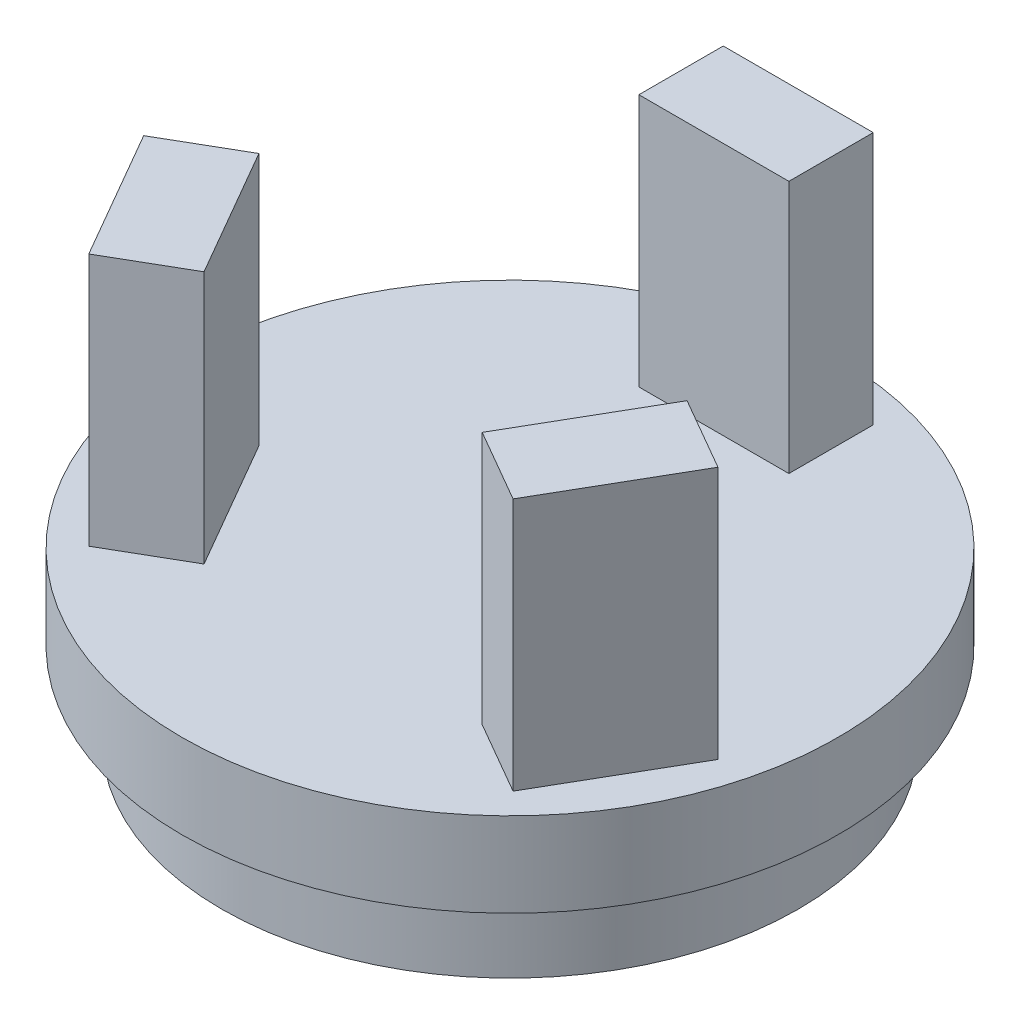
SolidWorks part; units mm, degrees
ref_plane "Plan de face" through (0, 0, 0) normal (0, 0, 1) x (1, 0, 0)
ref_plane "Plan de dessus" through (0, 0, 0) normal (0, 1, 0) x (1, 0, 0)
ref_plane "Plan de droite" through (0, 0, 0) normal (1, 0, 0) x (0, 0, -1)
sketch "Esquisse2" plane through (0, 0, 0) normal (0, 1, 0) x (1, 0, 0)
  circle A0 centre (50.8875, 23.7844) radius 61.5
  dimension "D2" = 123
extrude "Boss.-Extru.1" add sketch "Esquisse2" along normal blind 18
sketch "Esquisse3" plane through (0, 18, 0) normal (0, 1, 0) x (1, 0, 0)
  circle A0 centre (50.8875, 23.7844) radius 70
  circle A1 centre (50.8875, 23.7844) radius 61.5 construction
  dimension "D1" = 0
extrude "Boss.-Extru.2" add sketch "Esquisse3" along normal blind 18
sketch "Esquisse4" plane through (0, 36, 0) normal (0, 1, 0) x (1, 0, 0)
  line L0 (50.8875, 23.7844) -> (50.8875, 85.2844) construction
  line L1 (50.8875, 85.2844) -> (50.8875, 23.7844) construction
  line L2 (50.8875, 23.7844) -> (104.1481, -6.9656) construction
  line L3 (104.1481, -6.9656) -> (50.8875, 23.7844) construction
  line L4 (50.8875, 23.7844) -> (-2.373, -6.9656) construction
  line L5 (104.1481, -6.9656) -> (96.1481, -20.822)
  line L6 (96.1481, -20.822) -> (80.5596, -11.822)
  line L7 (80.5596, -11.822) -> (88.5596, 2.0344)
  line L8 (88.5596, 2.0344) -> (96.5596, 15.8908)
  line L9 (96.5596, 15.8908) -> (112.1481, 6.8908)
  line L10 (112.1481, 6.8908) -> (104.1481, -6.9656)
  line L11 (66.8875, 67.2844) -> (50.8875, 67.2844)
  line L12 (34.8875, 85.2844) -> (50.8875, 85.2844)
  line L13 (50.8875, 85.2844) -> (66.8875, 85.2844)
  line L14 (50.8875, 67.2844) -> (34.8875, 67.2844)
  line L15 (34.8875, 67.2844) -> (34.8875, 85.2844)
  line L16 (66.8875, 85.2844) -> (66.8875, 67.2844)
  line L17 (-10.373, 6.8908) -> (5.2154, 15.8908)
  line L18 (5.627, -20.822) -> (-2.373, -6.9656)
  line L19 (5.2154, 15.8908) -> (13.2154, 2.0344)
  line L20 (13.2154, 2.0344) -> (21.2154, -11.822)
  line L21 (-2.373, -6.9656) -> (-10.373, 6.8908)
  line L22 (21.2154, -11.822) -> (5.627, -20.822)
  circle A0 centre (50.8875, 23.7844) radius 61.5
  circle A1 centre (50.8875, 23.7844) radius 70 construction
  dimension "D1" = 0
  dimension "D2" = 123
  dimension "D3" = 120
  dimension "D4" = 120
  dimension "D5" = 120
  dimension "D6" = 16
  dimension "D7" = 16
  dimension "D8" = 90
  dimension "D9" = 90
  dimension "D10" = 18
extrude "Boss.-Extru.3" add sketch "Esquisse4" along normal blind 54 contours L17 A0 L22 L20 L19 | L16 A0 L15 L14 L11 | L6 A0 L9 L8 L7 | A0 L10 L9 | A0 L6 L5 | A0 L16 L13 | A0 L12 L15 | A0 L18 L22 | A0 L17 L21
sketch "Esquisse5" plane through (0, 36, 0) normal (0, 1, 0) x (1, 0, 0)
  line L0 (49.6658, -46.205) -> (52.1092, 93.7737) construction
  circle A0 centre (50.8875, 23.7844) radius 70 construction
  point P5 (50.8875, 23.7844)
